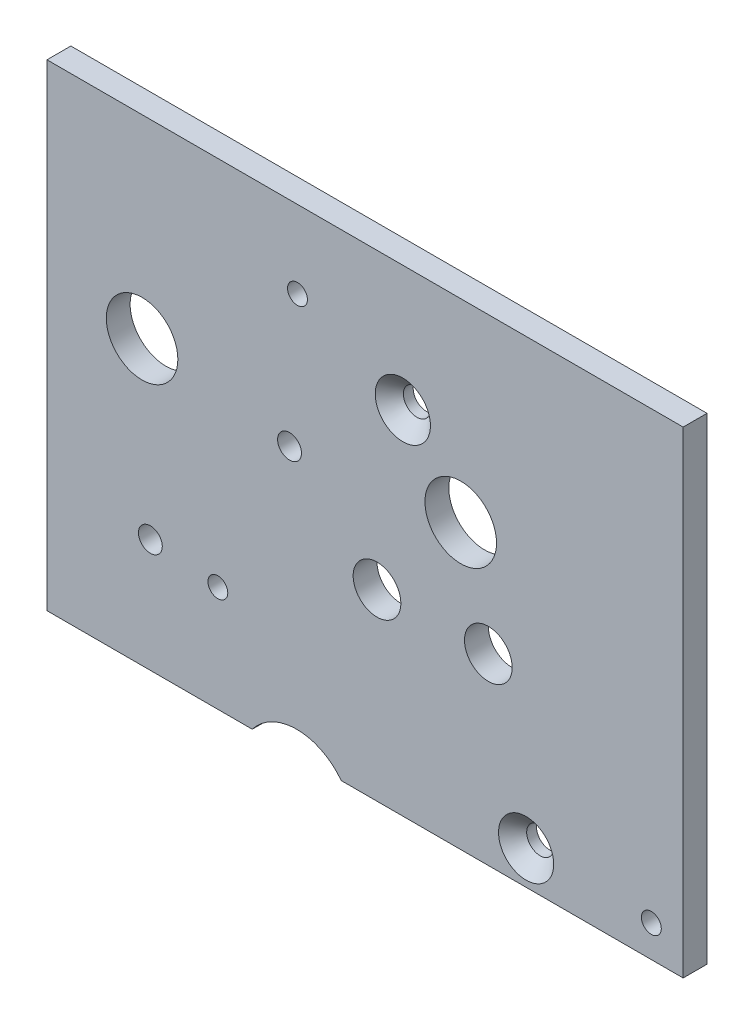
SolidWorks part; units mm, degrees
ref_plane "Спереди" through (0, 0, 0) normal (0, 0, 1) x (1, 0, 0)
ref_plane "Сверху" through (0, 0, 0) normal (0, 1, 0) x (1, 0, 0)
ref_plane "Справа" through (0, 0, 0) normal (1, 0, 0) x (0, 0, -1)
sketch "Эскиз1" plane through (0, 0, 53.2) normal (0, 0, 1) x (1, 0, 0)
  line L0 (-4.1022, 226.3533) -> (38.8934, 226.3533)
  line L1 (-41.1066, 226.3533) -> (-15.2889, 226.3533)
  line L2 (-41.1066, 226.3533) -> (-41.1066, 286.3533)
  line L3 (-41.1066, 286.3533) -> (38.8934, 286.3533)
  line L4 (38.8934, 226.3533) -> (38.8934, 286.3533)
  arc A0 (-4.1022, 226.3533) -> (-15.2889, 226.3533) centre (-9.6955, 222.1444) ccw
  circle A1 centre (0.3934, 249.4033) radius 3
  circle A2 centre (14.3934, 249.4033) radius 3
  circle A3 centre (-29.1505, 261.9561) radius 4.5
  circle A4 centre (10.9231, 261.9857) radius 4.5
  dimension "D3" = 9
  dimension "D4" = 9
  dimension "D1" = 80
  dimension "D2" = 60
extrude "Бобышка-Вытянуть1" add sketch "Эскиз1" along normal blind 3
sketch "Эскиз2" plane through (0, 0, 56.2) normal (0, 0, 1) x (1, 0, 0)
  circle A0 centre (-28.1066, 240.6033) radius 1.5 construction
  circle A1 centre (-28.1066, 240.6033) radius 1.5
  circle A2 centre (-10.6066, 259.5033) radius 1.5 construction
  circle A3 centre (-10.6066, 259.5033) radius 1.5
  circle A4 centre (3.6434, 270.6033) radius 1.25 construction
  circle A5 centre (3.6434, 270.6033) radius 1.25
  circle A6 centre (19.1434, 230.6033) radius 1.25 construction
  circle A7 centre (19.1434, 230.6033) radius 1.25
hole_wizard "CSK for M3 Hex Socket Countersunk Head Screw1" positions "3DSketch3" profile "Sketch3" countersink size "M3" standard "DIN" end condition through all
sketch3d "3DSketch3"
  point P6 (3.6434, 270.6033, 56.2)
  point P9 (19.1434, 230.6033, 56.2)
sketch "Sketch3" plane through (3.6434, 270.6033, 56.2) normal (1, 0, 0) x (0, -1, 0)
  line L0 (0, 0) -> (0, 3)
  line L1 (0, 3) -> (1.7, 3)
  line L2 (1.7, 3) -> (1.7, 1.77)
  line L3 (1.7, 1.77) -> (3.47, 0)
  line L5 (3.47, 0) -> (0, 0)
  line L6 (-1.7, 1.77) -> (-3.47, 0) construction
  line L11 (0, -6.35) -> (0, 107.95) construction
  dimension "Диаметр сквозного отверстия" = 3.4
  dimension "Глубина сквозного отверстия" = 3
  dimension "Диаметр передней зенковки" = 6.94
  dimension "Угол передней зенковки" = 90
extrude "Cut-Extrude1" cut sketch "Эскиз2" against normal blind 10
sketch "Sketch4" plane through (0, 0, 56.2) normal (0, 0, 1) x (1, 0, 0)
  circle A0 centre (-9.6066, 276.6033) radius 1.25
  circle A1 centre (-19.6207, 239.6533) radius 1.25
  circle A2 centre (34.8934, 230.3533) radius 1.25
  dimension "D1" = 2.5
  dimension "D2" = 2.5
  dimension "D3" = 2.5
extrude "Cut-Extrude2" cut sketch "Sketch4" against normal up to surface (3 mm away) up to face at (-26.6066, 240.6033, 53.2)
